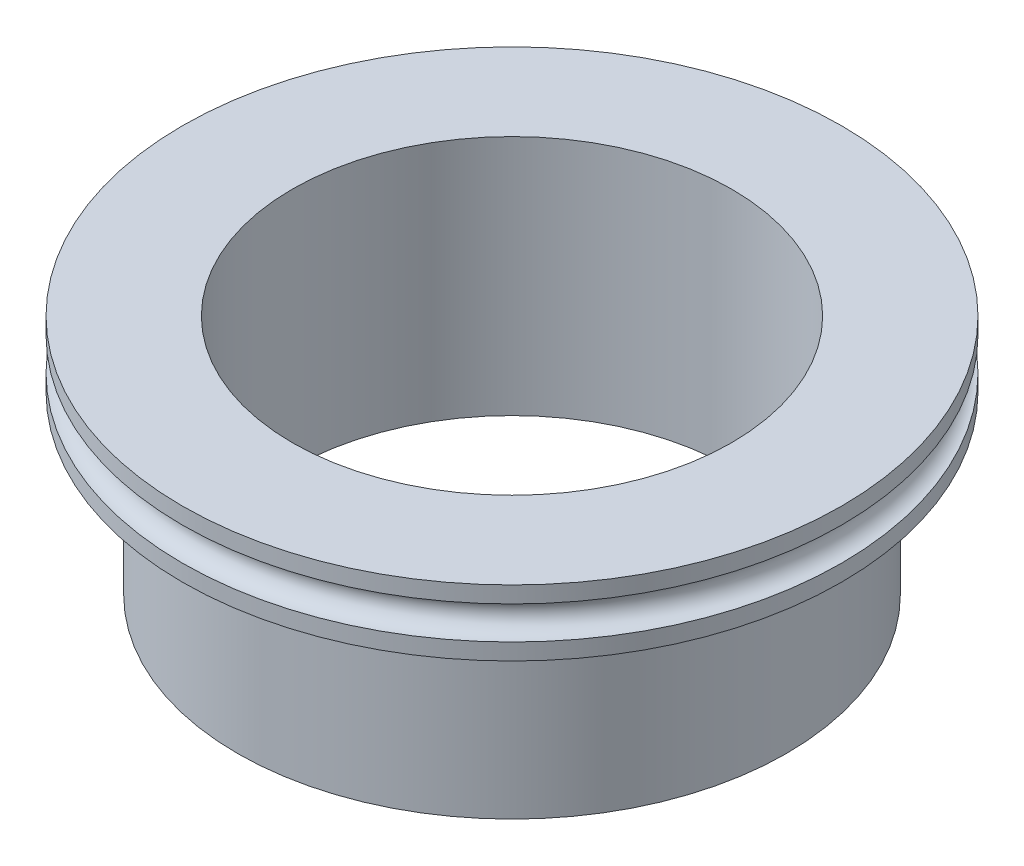
SolidWorks part; units mm, degrees
ref_plane "Alzado" through (0, 0, 0) normal (0, 0, 1) x (1, 0, 0)
ref_plane "Planta" through (0, 0, 0) normal (0, 1, 0) x (1, 0, 0)
ref_plane "Vista lateral" through (0, 0, 0) normal (1, 0, 0) x (0, 0, -1)
sketch "Croquis1" plane through (0, 0, 0) normal (0, 1, 0) x (1, 0, 0)
  circle A0 centre (0, 0) radius 15
  dimension "D1" = 30
extrude "Saliente-Extruir1" add sketch "Croquis1" along normal mid plane 3
ref_axis "Eje1" through (0, 1.5, 0) along (0, -1, 0)
sketch "Croquis2" plane through (0, 0, 0) normal (1, 0, 0) x (0, 0, -1)
  line L0 (15, -1.5) -> (15, 1.5) construction
  circle A0 centre (15, 0) radius 0.75
  dimension "D1" = 1.5
revolve "Cortar-Revolución1" cut sketch "Croquis2" angle 360 about axis through (0, 1.5, 0) along (0, -1, 0)
sketch "Croquis4" plane through (0, -1.5, 0) normal (0, -1, 0) x (1, 0, 0)
  circle A0 centre (0, 0) radius 12.5
  dimension "D1" = 25
extrude "Saliente-Extruir2" add sketch "Croquis4" along normal blind 8
sketch "Croquis3" plane through (0, 1.5, 0) normal (0, 1, 0) x (1, 0, 0)
  circle A0 centre (0, 0) radius 10
  dimension "D1" = 20
extrude "Cortar-Extruir1" cut sketch "Croquis3" against normal through all
